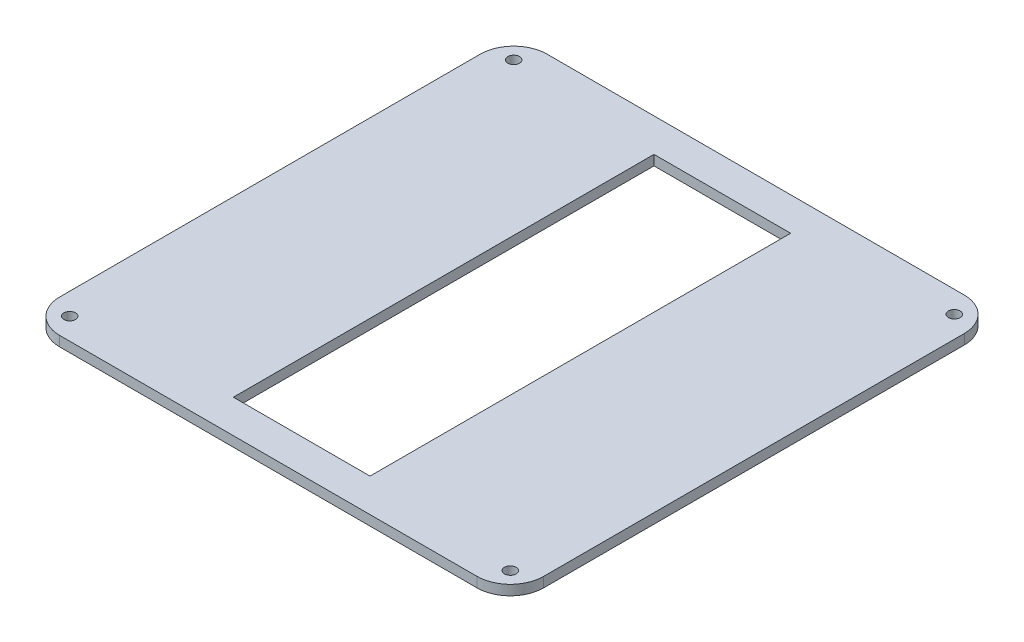
SolidWorks part; units mm, degrees
ref_plane "Plan de face" through (0, 0, 0) normal (0, 0, 1) x (1, 0, 0)
ref_plane "Plan de dessus" through (0, 0, 0) normal (0, 1, 0) x (1, 0, 0)
ref_plane "Plan de droite" through (0, 0, 0) normal (1, 0, 0) x (0, 0, -1)
sketch "Esquisse1" plane through (0, 0, 0) normal (0, 1, 0) x (1, 0, 0)
  line L0 (-72.6, -63.1) -> (-72.6, 63.1)
  line L1 (-62.6, -63.1) -> (62.6, -63.1) construction
  line L2 (-62.6, -63.1) -> (-62.6, 63.1) construction
  line L3 (-62.6, 63.1) -> (62.6, 63.1) construction
  line L4 (62.6, -63.1) -> (62.6, 63.1) construction
  line L5 (-62.6, -63.1) -> (62.6, 63.1) construction
  line L6 (-62.6, 63.1) -> (62.6, -63.1) construction
  line L7 (-62.6, 73.1) -> (62.6, 73.1)
  line L8 (72.6, -63.1) -> (72.6, 63.1)
  line L9 (-62.6, -73.1) -> (62.6, -73.1)
  line L10 (-72.6, -73.1) -> (-72.6, 73.1) construction
  line L11 (-72.6, -73.1) -> (72.6, -73.1) construction
  line L12 (72.6, -73.1) -> (72.6, 73.1) construction
  line L13 (-72.6, 73.1) -> (72.6, 73.1) construction
  line L14 (-66.1, 66.6) -> (66.1, 66.6) construction
  line L15 (66.1, -66.6) -> (66.1, 66.6) construction
  line L16 (-66.1, -66.6) -> (66.1, -66.6) construction
  line L17 (-66.1, -66.6) -> (-66.1, 66.6) construction
  line L18 (0, -1000) -> (0, 49000) construction
  line L19 (20.5, -1000) -> (20.5, -73.1)
  line L20 (-20.5, -1000) -> (-20.5, -73.1)
  line L21 (-20.5, 63.1) -> (20.5, 63.1)
  line L22 (-20.5, -63.1) -> (20.5, -63.1)
  line L23 (-20.5, 73.1) -> (-20.5, 49000)
  line L24 (20.5, 73.1) -> (20.5, 49000)
  line L25 (-20.5, -1000) -> (-20.5, 49000) construction
  line L26 (-20.5, -63.1) -> (-20.5, 63.1)
  line L27 (20.5, -1000) -> (20.5, 49000) construction
  line L28 (20.5, -63.1) -> (20.5, 63.1)
  arc A0 (-72.6, -63.1) -> (-62.6, -73.1) centre (-62.6, -63.1) ccw
  arc A1 (62.6, -73.1) -> (72.6, -63.1) centre (62.6, -63.1) ccw
  arc A2 (72.6, 63.1) -> (62.6, 73.1) centre (62.6, 63.1) ccw
  arc A3 (-62.6, 73.1) -> (-72.6, 63.1) centre (-62.6, 63.1) ccw
  circle A4 centre (-66.1, 66.6) radius 1.75
  circle A5 centre (66.1, 66.6) radius 1.75
  circle A6 centre (66.1, -66.6) radius 1.75
  circle A7 centre (-66.1, -66.6) radius 1.75
  point P0 (0, 0)
  dimension "D4" = 10
  dimension "D6" = 3.5
  dimension "D7" = 3.5
  dimension "D8" = 3.5
  dimension "D9" = 3.5
  dimension "D1" = 125.2
  dimension "D2" = 126.2
  dimension "D3" = 10
  dimension "D5" = 3.5
  dimension "D10" = 20.5
  dimension "D11" = 20.5
extrude "Boss.-Extru.1" add sketch "Esquisse1" along normal blind 3
